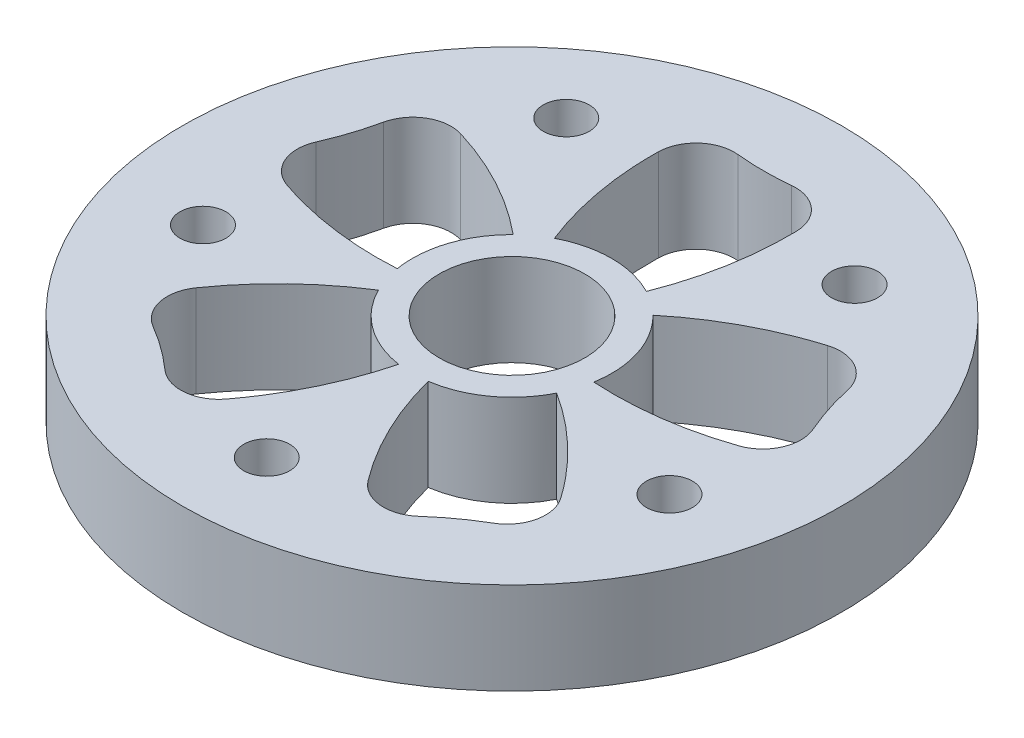
SolidWorks part; units mm, degrees
ref_plane "Front Plane" through (0, 0, 0) normal (0, 0, 1) x (1, 0, 0)
ref_plane "Top Plane" through (0, 0, 0) normal (0, 1, 0) x (1, 0, 0)
ref_plane "Right Plane" through (0, 0, 0) normal (1, 0, 0) x (0, 0, -1)
sketch "Sketch1" plane through (0, 0, 0) normal (0, 1, 0) x (1, 0, 0)
  line L0 (0, 40.7341) -> (0, -37.1377) construction
  line L1 (-30.776, 0) -> (49.0637, 0) construction
  circle A0 centre (0, 0) radius 9.5
  circle A1 centre (0, 0) radius 43
  circle A2 centre (0, 0) radius 32 construction
  circle A3 centre (0, -32) radius 3
  circle A4 centre (-30.4338, -9.8885) radius 3
  circle A5 centre (-18.8091, 25.8885) radius 3
  circle A6 centre (18.8091, 25.8885) radius 3
  circle A7 centre (30.4338, -9.8885) radius 3
  dimension "D1" = 86
  dimension "D2" = 19
  dimension "D3" = 64
  dimension "D4" = 6
  dimension "D5" = 5
extrude "Boss-Extrude1" add sketch "Sketch1" along normal mid plane 12
sketch "Sketch2" plane through (0, 6, 0) normal (0, 1, 0) x (1, 0, 0)
  line L0 (0, 0) -> (0, 50000) construction
  line L1 (0, 0) -> (50000, 0) construction
  arc A0 (-11.6328, -5.8033) -> (-1.9246, -12.8568) centre (0, 0) ccw
  arc A1 (-6, 11.5326) -> (-8.9979, 28.0889) centre (33.9953, 27.3243) cw
  arc A2 (-8.9979, 28.0889) -> (-3.5, 32.9751) centre (-3.9987, 28) cw
  arc A3 (-3.5, 32.9751) -> (3.5, 32.9751) centre (0, 67.8905) ccw
  arc A4 (6, 11.5326) -> (8.9979, 28.0889) centre (-33.9953, 27.3243) ccw
  arc A5 (8.9979, 28.0889) -> (3.5, 32.9751) centre (3.9987, 28) ccw
  arc A6 (12.8222, -2.1426) -> (29.4947, 0.1224) centre (15.4818, 40.7751) ccw
  arc A7 (29.4947, 0.1224) -> (32.4427, 6.8612) centre (27.8653, 4.8495) ccw
  arc A8 (30.2796, 13.5186) -> (32.4427, 6.8612) centre (64.5677, 20.9793) ccw
  arc A9 (23.9336, 17.2375) -> (30.2796, 13.5186) centre (25.3939, 12.4555) cw
  arc A10 (9.114, 9.2701) -> (23.9336, 17.2375) centre (36.492, -23.8878) cw
  arc A11 (1.9246, -12.8568) -> (9.2308, -28.0133) centre (43.5636, -2.1239) ccw
  arc A12 (9.2308, -28.0133) -> (16.5507, -28.7346) centre (13.223, -25.0029) ccw
  arc A13 (22.2138, -24.6201) -> (16.5507, -28.7346) centre (39.905, -54.9245) ccw
  arc A14 (23.7897, -17.4356) -> (22.2138, -24.6201) centre (19.693, -20.3021) cw
  arc A15 (11.6328, -5.8033) -> (23.7897, -17.4356) centre (-11.442, -42.0877) cw
  arc A16 (-11.6328, -5.8033) -> (-23.7897, -17.4356) centre (11.442, -42.0877) ccw
  arc A17 (-23.7897, -17.4356) -> (-22.2138, -24.6201) centre (-19.693, -20.3021) ccw
  arc A18 (-16.5507, -28.7346) -> (-22.2138, -24.6201) centre (-39.905, -54.9245) ccw
  arc A19 (-9.2308, -28.0133) -> (-16.5507, -28.7346) centre (-13.223, -25.0029) cw
  arc A20 (-1.9246, -12.8568) -> (-9.2308, -28.0133) centre (-43.5636, -2.1239) cw
  arc A21 (-9.114, 9.2701) -> (-23.9336, 17.2375) centre (-36.492, -23.8878) ccw
  arc A22 (-23.9336, 17.2375) -> (-30.2796, 13.5186) centre (-25.3939, 12.4555) ccw
  arc A23 (-32.4427, 6.8612) -> (-30.2796, 13.5186) centre (-64.5677, 20.9793) ccw
  arc A24 (-29.4947, 0.1224) -> (-32.4427, 6.8612) centre (-27.8653, 4.8495) cw
  arc A25 (-12.8222, -2.1426) -> (-29.4947, 0.1224) centre (-15.4818, 40.7751) cw
  arc A26 (1.9246, -12.8568) -> (11.6328, -5.8033) centre (0, 0) ccw
  arc A27 (12.8222, -2.1426) -> (9.114, 9.2701) centre (0, 0) ccw
  arc A28 (6, 11.5326) -> (-6, 11.5326) centre (0, 0) ccw
  arc A29 (-9.114, 9.2701) -> (-12.8222, -2.1426) centre (0, 0) ccw
  dimension "D1" = 26
  dimension "D3" = 5
  dimension "D4" = 43
  dimension "D8" = 5
  dimension "D2" = 7
  dimension "D5" = 28
  dimension "D6" = 7.9974
  dimension "D7" = 12
extrude "Cut-Extrude1" cut sketch "Sketch2" against normal through all both and the other way through all contours A29 A21 A22 A23 A24 A25 | A28 A4 A5 A3 A2 A1 | A27 A6 A7 A8 A9 A10 | A20 A0 A16 A17 A18 A19 | A26 A11 A12 A13 A14 A15
